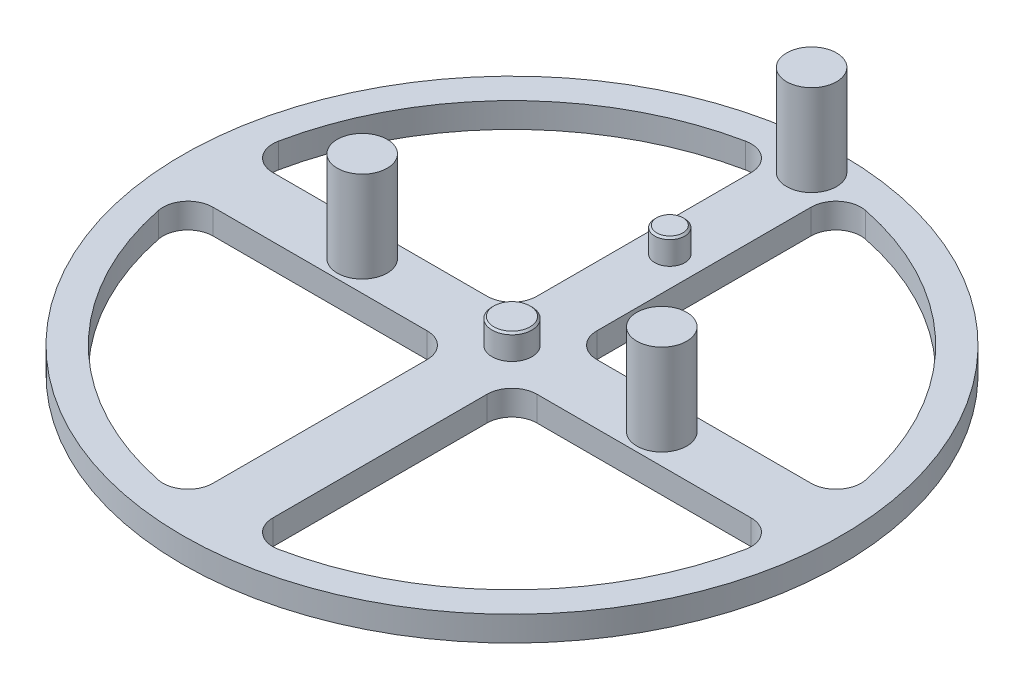
SolidWorks part; units mm, degrees
ref_plane "Front Plane" through (0, 0, 0) normal (0, 0, 1) x (1, 0, 0)
ref_plane "Top Plane" through (0, 0, 0) normal (0, 1, 0) x (1, 0, 0)
ref_plane "Right Plane" through (0, 0, 0) normal (1, 0, 0) x (0, 0, -1)
sketch "Sketch1" plane through (0, 0, 0) normal (0, 1, 0) x (1, 0, 0)
  line L0 (0, 0) -> (0, 66) construction
  line L1 (-6, -59.6992) -> (-6, -6)
  line L2 (6, -59.6992) -> (6, -6)
  line L3 (0, 0) -> (-50, 0) construction
  line L4 (-59.6992, -6) -> (-6, -6)
  line L5 (-59.6992, 6) -> (-6, 6)
  line L6 (6, 6) -> (6, 59.6992)
  line L7 (6, -6) -> (59.6992, -6)
  line L8 (-6, 6) -> (-6, 59.6992)
  line L9 (-6, -6) -> (-6, 6) construction
  line L10 (-6, 6) -> (6, 6) construction
  line L11 (6, 6) -> (59.6992, 6)
  circle A0 centre (0, 0) radius 66
  arc A1 (-6, 59.6992) -> (-59.6992, 6) centre (0, 0) ccw
  arc A2 (6, -59.6992) -> (59.6992, -6) centre (0, 0) ccw
  circle A3 centre (0, 31.6) radius 3 construction
  circle A4 centre (0, 0) radius 4 construction
  circle A5 centre (0, 0) radius 6 construction
  circle A6 centre (0, 31.6) radius 6 construction
  arc A7 (59.6992, 6) -> (6, 59.6992) centre (0, 0) ccw
  arc A8 (-59.6992, -6) -> (-6, -59.6992) centre (0, 0) ccw
  dimension "D1" = 6
  dimension "D2" = 132
  dimension "D3" = 6
  dimension "D4" = 8
  dimension "D6" = 2
  dimension "D5" = 31.6
extrude "Boss-Extrude1" add sketch "Sketch1" along normal blind 5
fillet "Fillet1" radius 5 12 edges at (-6, 2.5, 59.6992) (6, 2.5, 59.6992) (59.6992, 2.5, 6) (-6, 2.5, 6) (6, 2.5, 6) (-6, 2.5, -6) (6, 2.5, -6) (59.6992, 2.5, -6) (-59.6992, 2.5, 6) (-59.6992, 2.5, -6) (6, 2.5, -59.6992) (-6, 2.5, -59.6992)
sketch "Sketch2" plane through (0, 5, 0) normal (0, 1, 0) x (1, 0, 0)
  circle A0 centre (0, 0) radius 4
  circle A1 centre (0, 31.6) radius 3
  circle A2 centre (0, 31.6) radius 3 construction
  circle A3 centre (0, 0) radius 4 construction
  point P5 (0, 0)
extrude "Boss-Extrude2" add sketch "Sketch2" along normal blind 5
chamfer "Chamfer1" distance 0.375 angle 45 2 edges at (0, 10, 4) (0, 10, -28.6)
sketch "Sketch3" plane through (0, 5, 0) normal (0, 1, 0) x (1, 0, 0)
  line L0 (0, 0) -> (-30, 0) construction
  circle A0 centre (-30, 0) radius 5
  dimension "D1" = 10
  dimension "D2" = 30
extrude "Boss-Extrude3" add sketch "Sketch3" along normal blind 18.2
mirror "Mirror1" about plane through (0, 0, 0) normal (1, 0, 0) of "Boss-Extrude3"
sketch "Sketch4" plane through (0, 5, 0) normal (0, 1, 0) x (1, 0, 0)
  line L0 (0, 0) -> (0, 60) construction
  circle A0 centre (0, 60) radius 5
  circle A1 centre (-30, 0) radius 5 construction
  dimension "D1" = 60
extrude "Boss-Extrude4" add sketch "Sketch4" along normal up to surface (18.2 mm away) up to face at (30, 23.2, 5)
